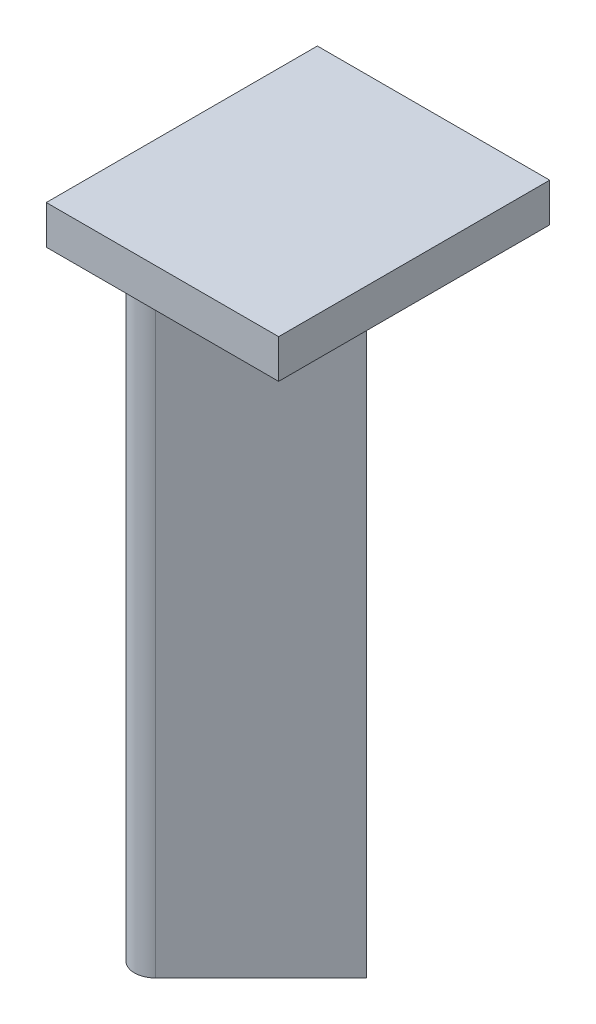
SolidWorks part; units mm, degrees
ref_plane "Front Plane" through (0, 0, 0) normal (0, 0, 1) x (1, 0, 0)
ref_plane "Top Plane" through (0, 0, 0) normal (0, 1, 0) x (1, 0, 0)
ref_plane "Right Plane" through (0, 0, 0) normal (1, 0, 0) x (0, 0, -1)
sketch "Sketch1" plane through (0, 0, 0) normal (0, 1, 0) x (1, 0, 0)
  line L0 (-0.7071, 0.7071) -> (-9.8288, 9.8288) construction
  line L1 (-0.7071, -0.7071) -> (-9.8288, -9.8288) construction
  line L2 (7.6368, 0) -> (-6.0104, 13.6472) construction
  line L3 (7.6368, 0) -> (-6.0104, -13.6472) construction
  line L4 (0, 0) -> (7.6368, 0) construction
  line L6 (0, 0) -> (-9.8288, -9.8288) construction
  line L7 (0, 0) -> (-9.8288, 9.8288) construction
  line L11 (-0.707, 0.7353) -> (-9.8146, 9.8429)
  line L12 (7.6085, 0) -> (-6.0245, 13.633)
  line L13 (7.6085, 0) -> (-6.0245, -13.633)
  line L14 (-0.707, -0.7353) -> (-9.8146, -9.8429)
  arc A0 (-9.8288, 9.8288) -> (-6.0104, 13.6472) centre (-7.9196, 11.738) cw construction
  arc A1 (-6.0104, -13.6472) -> (-9.8288, -9.8288) centre (-7.9196, -11.738) cw construction
  arc A2 (-0.7071, -0.7071) -> (-0.7071, 0.7071) centre (0, 0) ccw construction
  arc A6 (-9.8146, 9.8429) -> (-6.0245, 13.633) centre (-7.9196, 11.738) cw
  arc A7 (-6.0245, -13.633) -> (-9.8146, -9.8429) centre (-7.9196, -11.738) cw
  arc A8 (-0.707, -0.7353) -> (-0.707, 0.7353) centre (0, 0) ccw
  dimension "D4" = 2
  dimension "D2" = 19.3
  dimension "D3" = 19.3
extrude "Boss-Extrude1" add sketch "Sketch1" along normal blind 78
sketch "Sketch2" plane through (0, 78, 0) normal (0, 1, 0) x (1, 0, 0)
  line L1 (-16.7774, -16.9556) -> (13.2226, -16.9556)
  line L2 (-16.7774, -16.9556) -> (-16.7774, 18.0444)
  line L3 (-16.7774, 18.0444) -> (13.2226, 18.0444)
  line L4 (13.2226, -16.9556) -> (13.2226, 18.0444)
  dimension "D1" = 35
  dimension "D2" = 30
extrude "Boss-Extrude2" add sketch "Sketch2" along normal blind 5
